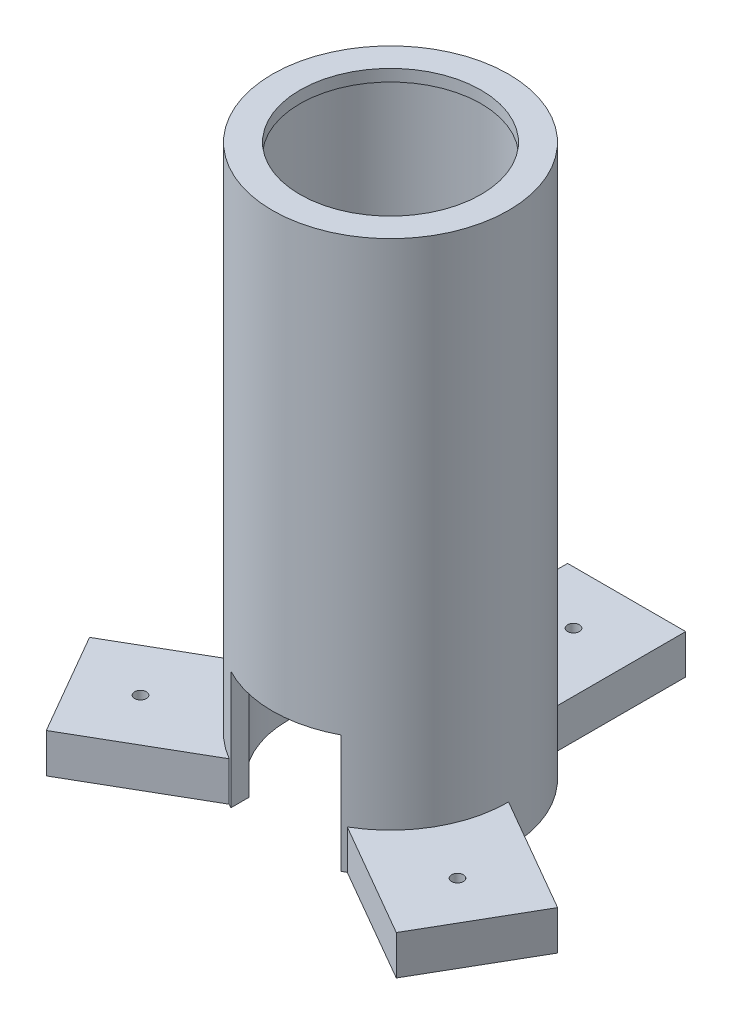
SolidWorks part; units mm, degrees
ref_plane "Front Plane" through (0, 0, 0) normal (0, 0, 1) x (1, 0, 0)
ref_plane "Top Plane" through (0, 0, 0) normal (0, 1, 0) x (1, 0, 0)
ref_plane "Right Plane" through (0, 0, 0) normal (1, 0, 0) x (0, 0, -1)
sketch "Sketch1" plane through (0, 0, 0) normal (0, 1, 0) x (1, 0, 0)
  circle A0 centre (0, 0) radius 13
  circle A1 centre (0, 0) radius 15
  dimension "D1" = 26
  dimension "D2" = 30
extrude "Boss-Extrude1" add sketch "Sketch1" along normal blind 68.58
sketch "Sketch2" plane through (0, 68.58, 0) normal (0, 1, 0) x (1, 0, 0)
  circle A0 centre (0, 0) radius 11.5
  circle A1 centre (0, 0) radius 15
  circle A2 centre (0, 0) radius 15
  dimension "D2" = 23
  dimension "D1" = 0
extrude "Boss-Extrude2" add sketch "Sketch2" along normal blind 1.5
sketch "Sketch3" plane through (0, 0, 0) normal (0, -1, 0) x (1, 0, 0)
  line L0 (-7, 0) -> (7, 0)
  line L2 (7, 0) -> (7, 15.5914)
  line L3 (7, 15.5914) -> (-7, 15.5914)
  line L4 (-7, 0) -> (-7, 15.5914)
  line L5 (0, 0) -> (-7, 15.5914) construction
  line L6 (7, 15.5914) -> (0, 0) construction
  point P0 (0, 0)
  point P2 (0, 15.5914)
  dimension "D1" = 14
extrude "Cut-Extrude1" cut sketch "Sketch3" against normal blind 15
sketch "Sketch4" plane through (0, 0, 0) normal (0, -1, 0) x (1, 0, 0)
  line L2 (-7.5, -12.9904) -> (-7.5, -30)
  line L3 (-7.5, -30) -> (7.5, -30)
  line L4 (7.5, -12.9904) -> (7.5, -30)
  line L5 (0, -15) -> (7.5, -30) construction
  line L6 (-7.5, -30) -> (0, -15) construction
  arc A0 (-7, 13.2665) -> (7, 13.2665) centre (0, 0) ccw construction
  arc A1 (-7.5, -12.9904) -> (7.5, -12.9904) centre (0, 0) ccw
  circle A2 centre (0, -23.25) radius 0.75
  point P0 (0, -15)
  dimension "D3" = 1.5
  dimension "D1" = 15
  dimension "D2" = 15
  dimension "D4" = 6.75
extrude "Boss-Extrude3" add sketch "Sketch4" against normal blind 5
pattern_circular "CirPattern1" count 3 every 120 about axis through (0, 0, 0) along (0, 1, 0) of "Boss-Extrude3"
